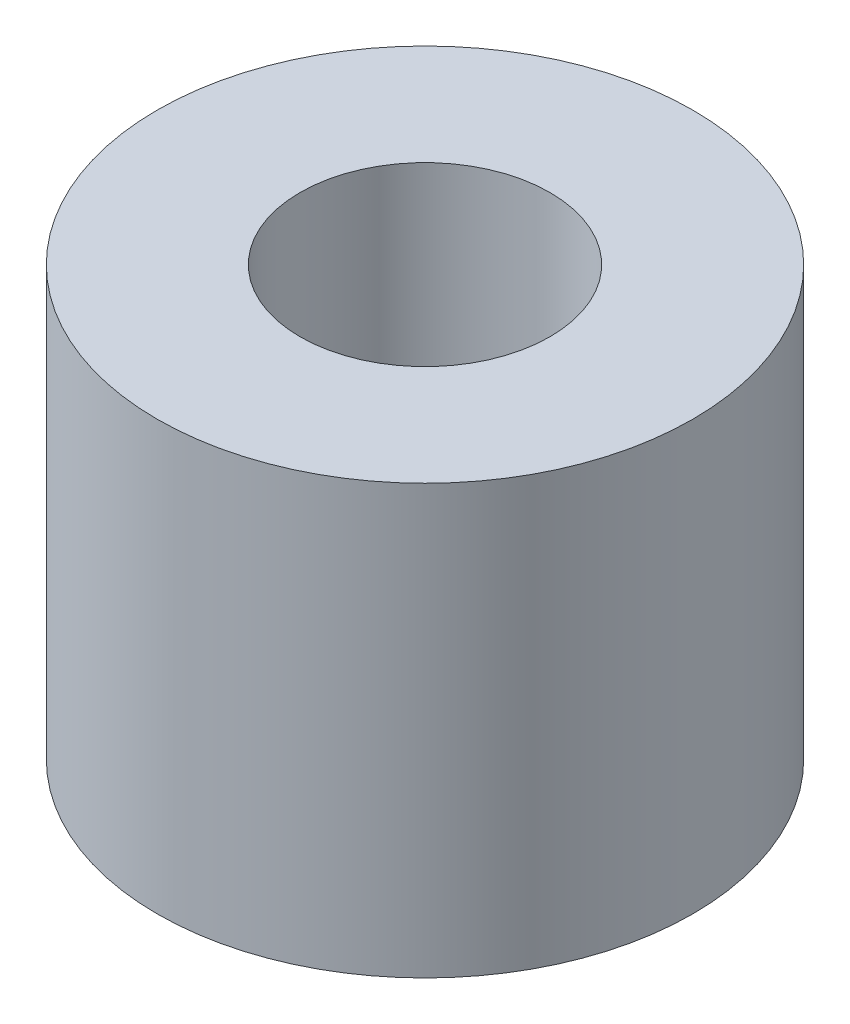
SolidWorks part; units mm, degrees
material "Alloy Steel (SS)"
ref_plane "Front Plane" through (0, 0, 0) normal (0, 0, 1) x (1, 0, 0)
ref_plane "Top Plane" through (0, 0, 0) normal (0, 1, 0) x (1, 0, 0)
ref_plane "Right Plane" through (0, 0, 0) normal (1, 0, 0) x (0, 0, -1)
sketch "Sketch1" plane through (0, 0, 0) normal (0, 1, 0) x (1, 0, 0)
  circle A0 centre (0, 0) radius 23.8125
  circle A1 centre (0, 0) radius 11.1125
  dimension "D1" = 22.225
  dimension "D2" = 12.7
extrude "Boss-Extrude1" add sketch "Sketch1" along normal blind 38.1
